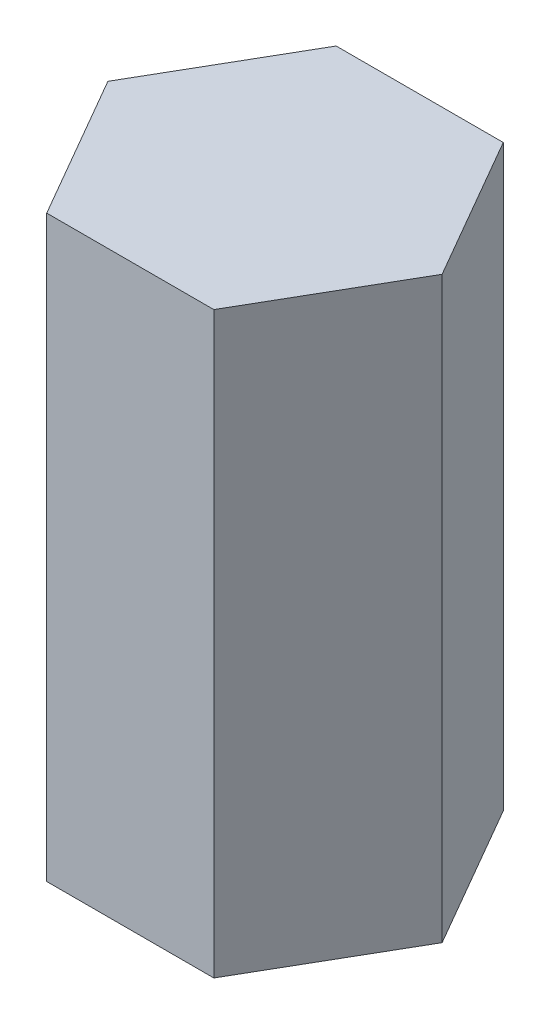
SolidWorks part; units mm, degrees
ref_plane "前视基准面" through (0, 0, 0) normal (0, 0, 1) x (1, 0, 0)
ref_plane "上视基准面" through (0, 0, 0) normal (0, 1, 0) x (1, 0, 0)
ref_plane "右视基准面" through (0, 0, 0) normal (1, 0, 0) x (0, 0, -1)
sketch "草图1" plane through (0, 0, 0) normal (0, 1, 0) x (1, 0, 0)
  line L1 (8.6603, 0) -> (4.3301, 7.5)
  line L2 (4.3301, 7.5) -> (-4.3301, 7.5)
  line L3 (-4.3301, 7.5) -> (-8.6603, 0)
  line L4 (-8.6603, 0) -> (-4.3301, -7.5)
  line L5 (-4.3301, -7.5) -> (4.3301, -7.5)
  line L6 (4.3301, -7.5) -> (8.6603, 0)
  circle A0 centre (0, 0) radius 7.5 construction
extrude "凸台-拉伸1" add sketch "草图1" along normal blind 30
